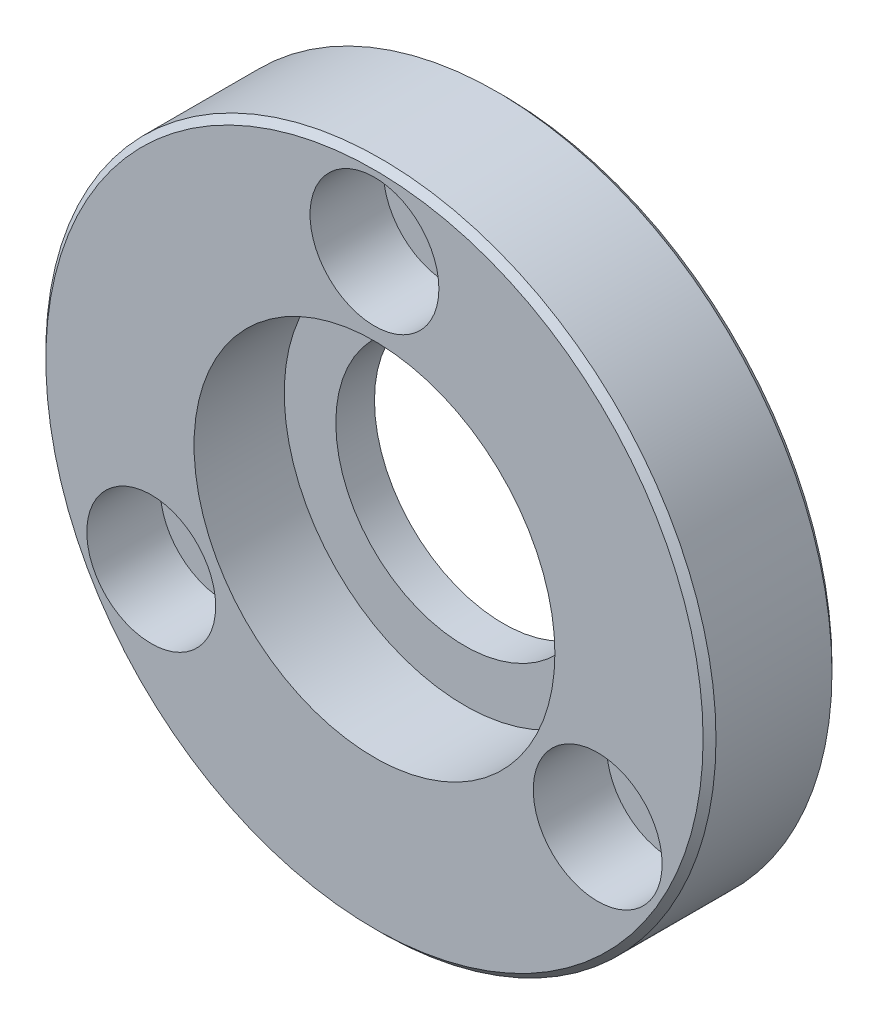
SolidWorks part; units mm, degrees
ref_plane "前视基准面" through (0, 0, 0) normal (0, 0, 1) x (1, 0, 0)
ref_plane "上视基准面" through (0, 0, 0) normal (0, 1, 0) x (1, 0, 0)
ref_plane "右视基准面" through (0, 0, 0) normal (1, 0, 0) x (0, 0, -1)
sketch "草图1" plane through (0, 0, 0) normal (0, 0, 1) x (1, 0, 0)
  circle A0 centre (0, 0) radius 26
extrude "凸台-拉伸1" add sketch "草图1" along normal mid plane 10
sketch "草图2" plane through (0, 0, 5) normal (0, 0, 1) x (1, 0, 0)
  circle A0 centre (0, 0) radius 14
extrude "切除-拉伸1" cut sketch "草图2" against normal blind 7
sketch "草图3" plane through (0, 0, -2) normal (0, 0, 1) x (1, 0, 0)
  circle A0 centre (0, 0) radius 10
extrude "切除-拉伸2" cut sketch "草图3" against normal through all
hole_wizard "打孔尺寸根据内六角圆柱头螺钉的类型1" positions "草图5" profile "草图4" counterbore size "M5" standard "GB" end condition through all
sketch "草图5" plane through (0, 0, 5) normal (0, 0, 1) x (1, 0, 0)
  point P0 (0, 20)
  dimension "D1" = 20
sketch "草图4" plane through (0, 20, 5) normal (1, 0, 0) x (0, -1, 0)
  line L0 (0, 0) -> (0, 10)
  line L1 (0, 10) -> (2.75, 10)
  line L3 (2.75, 10) -> (2.75, 5.7)
  line L4 (2.75, 5.7) -> (5, 5.7)
  line L5 (5, 5.7) -> (5, 0)
  line L7 (5, 0) -> (0, 0)
  line L11 (0, -6.35) -> (0, 107.95) construction
  dimension "通孔孔直径" = 5.5
  dimension "通孔孔深度" = 10
  dimension "柱形沉头孔直径" = 10
  dimension "柱形沉头孔深度" = 5.7
chamfer "倒角1" distance 0.5 angle 45 2 edges at (26, 0, -5) (26, 0, 5)
pattern_circular "阵列(圆周)1" count 3 over 360 about axis through (0, 0, 0) along (0, 0, 1) of "打孔尺寸根据内六角圆柱头螺钉的类型1"
